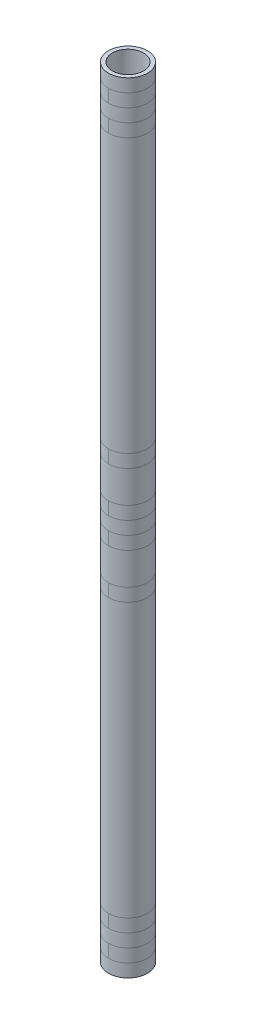
SolidWorks part; units mm, degrees
material "6063-O"
ref_plane "Front Plane" through (0, 0, 0) normal (0, 0, 1) x (1, 0, 0)
ref_plane "Top Plane" through (0, 0, 0) normal (0, 1, 0) x (1, 0, 0)
ref_plane "Right Plane" through (0, 0, 0) normal (1, 0, 0) x (0, 0, -1)
sketch "Sketch1" plane through (0, 0, 0) normal (0, 1, 0) x (1, 0, 0)
  circle A0 centre (0, 0) radius 15
  dimension "D1" = 30
extrude "Boss-Extrude1" add sketch "Sketch1" along normal blind 600
sketch "Sketch5" plane through (0, 600, 0) normal (0, 1, 0) x (1, 0, 0)
  circle A0 centre (0, 0) radius 12
  dimension "D1" = 24
extrude "Cut-Extrude1" cut sketch "Sketch5" against normal blind 600
ref_plane "Plane1" through (30, 0, 0) normal (1, 0, 0) x (0, 0, -1)
sketch "Sketch6" plane through (30, 0, 0) normal (1, 0, 0) x (0, 0, -1)
  line L0 (-15, 0) -> (15, 0) construction
  line L1 (-15, 600) -> (-15, 0) construction
  circle A0 centre (0, 279.5) radius 2.5
  circle A1 centre (0, 325.5) radius 2.5
  circle A2 centre (25, 300) radius 2.5
  dimension "D1" = 279.5
  dimension "D3" = 15
  dimension "D4" = 40
  dimension "D5" = 46
  dimension "D6" = 300
  dimension "D2" = 15
sketch "Sketch10" plane through (30, 0, 0) normal (1, 0, 0) x (0, 0, -1)
  line L0 (-15, 10) -> (15, 10)
  line L1 (-15, 600) -> (-15, 0) construction
  line L2 (15, 0) -> (15, 600) construction
  line L3 (15, 10) -> (15, 20)
  line L4 (15, 20) -> (-15, 20)
  line L5 (-15, 20) -> (-15, 10)
  line L6 (-15, 590) -> (15, 590)
  line L7 (15, 590) -> (15, 580)
  line L8 (15, 580) -> (-15, 580)
  line L9 (-15, 580) -> (-15, 590)
  line L10 (-15, 570) -> (15, 570)
  line L11 (15, 570) -> (15, 560)
  line L12 (15, 560) -> (-15, 560)
  line L13 (-15, 560) -> (-15, 570)
  line L14 (-15, 30) -> (-15, 40)
  line L15 (-15, 40) -> (15, 40)
  line L16 (15, 40) -> (15, 30)
  line L17 (15, 30) -> (-15, 30)
  line L18 (-15, 0) -> (15, 0) construction
  line L19 (15, 600) -> (-15, 600) construction
  line L20 (-15, 295) -> (15, 295)
  line L21 (15, 295) -> (15, 285)
  line L22 (15, 285) -> (-15, 285)
  line L23 (-15, 285) -> (-15, 295)
  line L24 (-15, 315) -> (15, 315)
  line L25 (15, 315) -> (15, 305)
  line L26 (15, 305) -> (-15, 305)
  line L27 (-15, 305) -> (-15, 315)
  dimension "D1" = 10
  dimension "D2" = 10
  dimension "D3" = 10
  dimension "D4" = 10
  dimension "D5" = 10
  dimension "D6" = 10
  dimension "D7" = 10
  dimension "D8" = 10
  dimension "D9" = 10
  dimension "D10" = 10
  dimension "D11" = 10
split line "Split Line2"
sketch "Sketch11" plane through (30, 0, 0) normal (1, 0, 0) x (0, 0, -1)
  line L0 (-15, 349.58) -> (-15, 339.58)
  line L1 (-15, 560) -> (-15, 315) construction
  line L2 (-15, 260.42) -> (-15, 250.42)
  line L3 (-15, 285) -> (-15, 40) construction
  line L4 (-15, 285) -> (15, 285) construction
  line L5 (15, 315) -> (-15, 315) construction
  line L6 (-15, 349.58) -> (0, 349.58)
  line L8 (0, 339.58) -> (-15, 339.58)
  line L9 (-15, 260.42) -> (0, 260.42)
  line L11 (0, 250.42) -> (-15, 250.42)
  line L12 (0, 349.58) -> (15, 349.58)
  line L13 (15, 315) -> (15, 560) construction
  line L14 (15, 349.58) -> (15, 339.58)
  line L15 (15, 339.58) -> (0, 339.58)
  line L16 (0, 260.42) -> (15, 260.42)
  line L17 (15, 40) -> (15, 285) construction
  line L18 (15, 260.42) -> (15, 250.42)
  line L19 (15, 250.42) -> (0, 250.42)
  dimension "D1" = 24.58
  dimension "D2" = 10
  dimension "D3" = 24.58
  dimension "D4" = 10
split line "Split Line6"
ref_plane "Plane2" through (0, 0, 30) normal (0, 0, 1) x (1, 0, 0)
sketch "Sketch9" plane through (0, 0, 30) normal (0, 0, 1) x (1, 0, 0)
  line L0 (-17.7777, 586.4464) -> (17.9432, 586.4464)
  line L1 (17.9432, 586.4464) -> (17.9432, 538.4114)
  line L2 (17.9432, 538.4114) -> (-17.7777, 538.4114)
  line L3 (-17.7777, 538.4114) -> (-17.7777, 586.4464)
  line L4 (-17.7777, 10.5086) -> (17.9432, 10.5086)
  line L5 (17.9432, 10.5086) -> (17.9432, 58.7449)
  line L6 (17.9432, 58.7449) -> (-17.7777, 58.7449)
  line L7 (-17.7777, 58.7449) -> (-17.7777, 10.5086)
  circle A0 centre (-7.8259, 575.72) radius 2.5
  circle A1 centre (7.9699, 575.72) radius 2.5
  circle A2 centre (-7.8259, 559.1861) radius 2.5
  circle A3 centre (7.9699, 559.1861) radius 2.5
  circle A4 centre (-7.8259, 45.6469) radius 2.5
  circle A5 centre (7.9699, 45.6469) radius 2.5
  circle A6 centre (7.9699, 28.7529) radius 2.5
  circle A7 centre (-7.8259, 28.7529) radius 2.5
